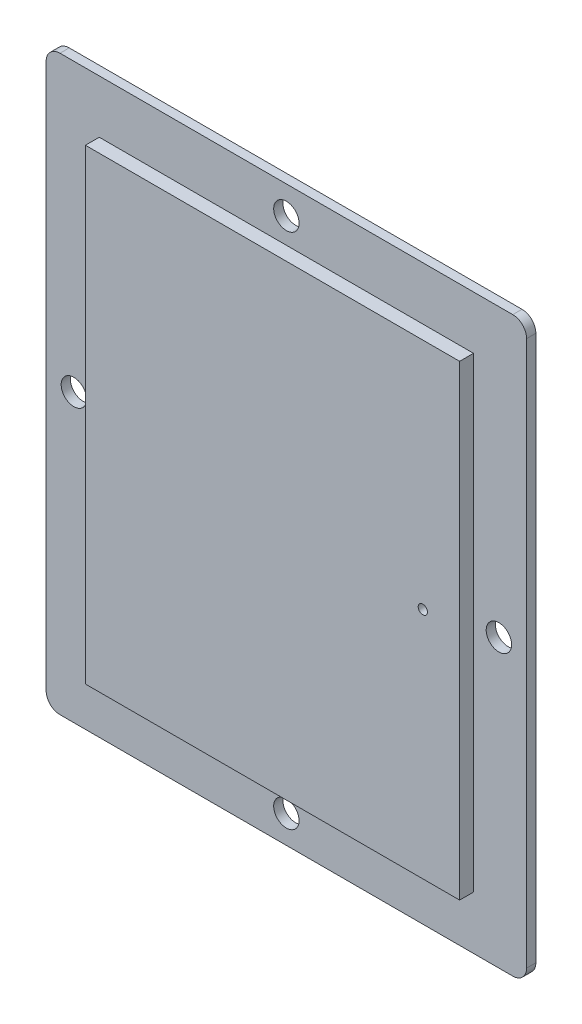
SolidWorks part; units mm, degrees
ref_plane "Front Plane" through (0, 0, 0) normal (0, 0, 1) x (1, 0, 0)
ref_plane "Top Plane" through (0, 0, 0) normal (0, 1, 0) x (1, 0, 0)
ref_plane "Right Plane" through (0, 0, 0) normal (1, 0, 0) x (0, 0, -1)
sketch "Sketch1" plane through (0, 0, 0) normal (0, 0, 1) x (1, 0, 0)
  line L1 (0, 0) -> (104, 0)
  line L2 (0, 0) -> (0, 124)
  line L3 (0, 124) -> (104, 124)
  line L4 (104, 0) -> (104, 124)
  circle A0 centre (101, 62) radius 2.75
  dimension "D2" = 5.5
  dimension "D3" = 62
  dimension "D4" = 62
  dimension "D5" = 3
  dimension "D1" = 104
extrude "Boss-Extrude1" add sketch "Sketch1" along normal blind 2 contours L3 L4 L1 L2
ref_plane "Plane1" through (104, 124, 2) normal (1, 0, 0) x (0, 0, -1)
sketch "Sketch3" plane through (104, 124, 2) normal (1, 0, 0) x (0, 0, -1)
sketch "Sketch4" plane through (0, 0, 2) normal (0, 0, 1) x (1, 0, 0)
  line L0 (0, 0) -> (0, 124) construction
  line L1 (11.5, 11.5) -> (92.5, 11.5)
  line L2 (11.5, 11.5) -> (11.5, 112.5)
  line L3 (11.5, 112.5) -> (92.5, 112.5)
  line L4 (92.5, 11.5) -> (92.5, 112.5)
  line L5 (11.5, 11.5) -> (92.5, 112.5) construction
  line L6 (11.5, 112.5) -> (92.5, 11.5) construction
  line L7 (104, 0) -> (104, 124) construction
  line L8 (0, 124) -> (104, 124) construction
  line L9 (0, 0) -> (104, 0) construction
  point P0 (52, 62)
  dimension "D1" = 101
  dimension "D2" = 81
  dimension "D3" = 11.5
  dimension "D4" = 11.5
  dimension "D5" = 11.5
  dimension "D6" = 11.5
extrude "Boss-Extrude2" add sketch "Sketch4" along normal blind 3
sketch "Sketch5" plane through (0, 0, 5) normal (0, 0, 1) x (1, 0, 0)
  line L0 (92.5, 112.5) -> (11.5, 112.5) construction
  line L1 (11.5, 11.5) -> (92.5, 11.5) construction
  circle A0 centre (84.5332, 62) radius 1
  dimension "D1" = 2
  dimension "D3" = 50.5
  dimension "D2" = 50.5
extrude "Cut-Extrude1" cut sketch "Sketch5" against normal through all contours A0
fillet "Fillet1" radius 3 4 edges at (104, 124, 1) (0, 124, 1) (0, 0, 1) (104, 0, 1)
sketch "Sketch6" plane through (0, 0, 2) normal (0, 0, 1) x (1, 0, 0)
  line L0 (3, 124) -> (101, 124) construction
  line L1 (3, 0) -> (101, 0) construction
  line L2 (92.5, 11.5) -> (92.5, 112.5) construction
  line L3 (104, 3) -> (104, 121) construction
  line L4 (0, 3) -> (0, 121) construction
  line L5 (11.5, 112.5) -> (11.5, 11.5) construction
  circle A0 centre (98, 62) radius 2.75
  circle A1 centre (6, 62) radius 2.75
  dimension "D1" = 5.5
  dimension "D4" = 5.5
  dimension "D5" = 6
  dimension "D6" = 5.5
  dimension "D7" = 6
  dimension "D8" = 5.5
  dimension "D9" = 62
  dimension "D10" = 62
  dimension "D2" = 62
  dimension "D3" = 62
sketch "Sketch9" plane through (0, 0, 2) normal (0, 0, 1) x (1, 0, 0)
  line L0 (11.5, 11.5) -> (92.5, 11.5) construction
  line L1 (3, 0) -> (101, 0) construction
  line L2 (0, 3) -> (0, 121) construction
  line L3 (104, 3) -> (104, 121) construction
  line L4 (11.5, 112.5) -> (11.5, 11.5) construction
  line L5 (92.5, 11.5) -> (92.5, 112.5) construction
  line L6 (92.5, 112.5) -> (11.5, 112.5) construction
  line L7 (3, 124) -> (101, 124) construction
  circle A0 centre (52, 6) radius 2.75
  circle A1 centre (52, 118) radius 2.75
  dimension "D1" = 5.5
  dimension "D2" = 5.5
  dimension "D3" = 6
  dimension "D4" = 52
  dimension "D5" = 52
  dimension "D8" = 5.5
  dimension "D9" = 5.5
  dimension "D10" = 6
  dimension "D11" = 52
  dimension "D12" = 52
  dimension "D6" = 11.5
  dimension "D7" = 11.5
extrude "Cut-Extrude3" cut sketch "Sketch6" against normal through all
extrude "Cut-Extrude4" cut sketch "Sketch9" against normal through all
